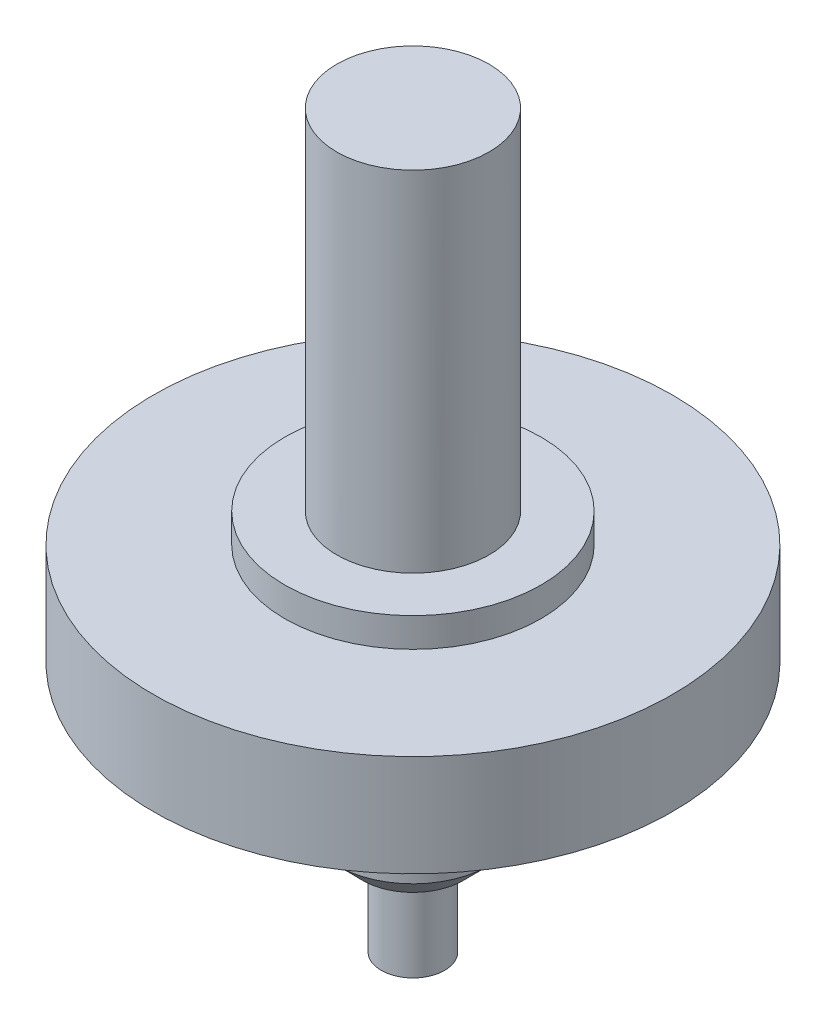
SolidWorks part; units mm, degrees
ref_plane "正面" through (0, 0, 0) normal (0, 0, 1) x (1, 0, 0)
ref_plane "平面" through (0, 0, 0) normal (0, 1, 0) x (1, 0, 0)
ref_plane "右側面" through (0, 0, 0) normal (1, 0, 0) x (0, 0, -1)
sketch "ｽｹｯﾁ1" plane through (0, 0, 0) normal (0, 0, 1) x (1, 0, 0)
  line L0 (0, 0) -> (0, 42.3)
  line L1 (0, 42.3) -> (3, 42.3)
  line L2 (3, 42.3) -> (3, 15.05)
  line L3 (3, 15.05) -> (5.05, 15.05)
  line L4 (5.05, 15.05) -> (5.05, 13.9)
  line L5 (5.05, 13.9) -> (10.225, 13.9)
  line L6 (10.225, 13.9) -> (10.225, 9.9)
  line L7 (10.225, 9.9) -> (3, 9.9)
  line L8 (3, 9.9) -> (3, 4.45)
  line L9 (2, 3.45) -> (1.25, 3.45)
  line L10 (1.25, 3.45) -> (1.25, 0)
  line L11 (1.25, 0) -> (0, 0)
  line L12 (3, 4.45) -> (2, 3.45)
  point P10 (3, 3.45)
  dimension "D1" = 3
  dimension "D2" = 5.05
  dimension "D3" = 10.225
  dimension "D4" = 1.25
  dimension "D5" = 27.25
  dimension "D6" = 1.15
  dimension "D7" = 4
  dimension "D8" = 3.45
  dimension "D9" = 6.45
  dimension "D10" = 42.3
revolve "回転1" add sketch "ｽｹｯﾁ1" angle 360 about L0
sketch "ｽｹｯﾁ2" plane through (0, 42.3, 0) normal (0, 1, 0) x (1, 0, 0)
  line L0 (-1.6583, 2.5) -> (1.6583, 2.5)
  circle A0 centre (0, 0) radius 3 construction
  circle A2 centre (0, 0) radius 3
  arc A3 (1.6583, 2.5) -> (-1.6583, 2.5) centre (0, 0) ccw
  dimension "D2" = 2.5
  dimension "D1" = 0
extrude "ｶｯﾄ - 押し出し1" cut sketch "ｽｹｯﾁ2" against normal blind 12
sketch "ｽｹｯﾁ3" plane through (0, 42.3, 0) normal (0, 1, 0) x (1, 0, 0)
  circle A0 centre (0, 0) radius 3
  circle A1 centre (0, 0) radius 3 construction
extrude "ｶｯﾄ - 押し出し2" cut sketch "ｽｹｯﾁ3" against normal blind 13.5
